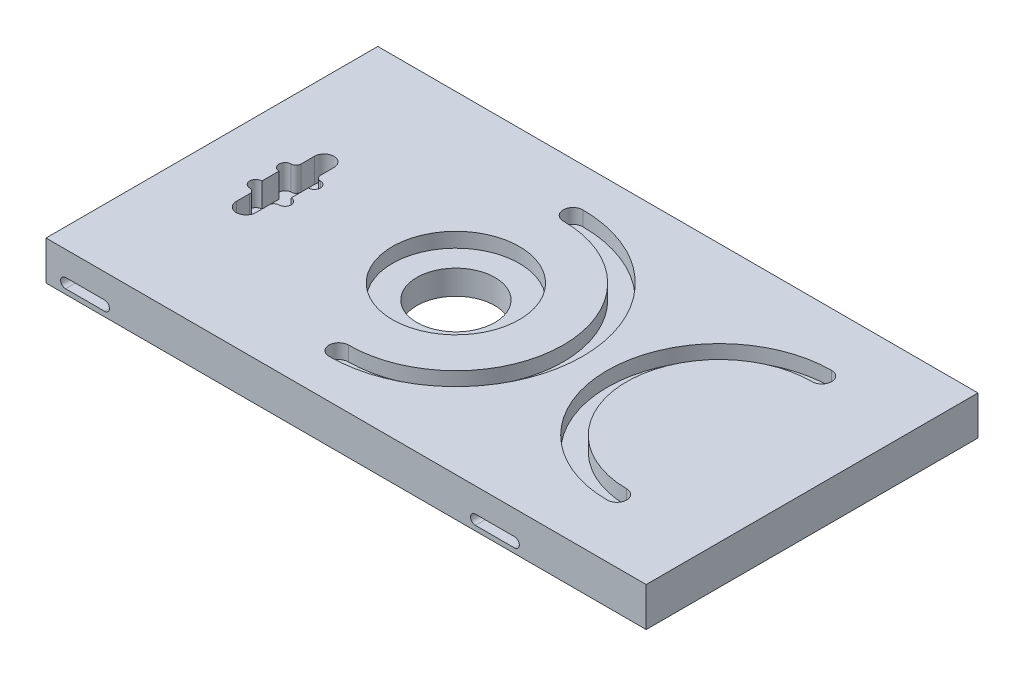
SolidWorks part; units mm, degrees
material "1060 Alloy"
ref_plane "Front Plane" through (0, 0, 0) normal (0, 0, 1) x (1, 0, 0)
ref_plane "Top Plane" through (0, 0, 0) normal (0, 1, 0) x (1, 0, 0)
ref_plane "Right Plane" through (0, 0, 0) normal (1, 0, 0) x (0, 0, -1)
sketch "Sketch1" plane through (0, 0, 0) normal (0, 1, 0) x (1, 0, 0)
  line L1 (-61.5, 34) -> (61.5, 34)
  line L2 (-61.5, 34) -> (-61.5, -34)
  line L3 (-61.5, -34) -> (61.5, -34)
  line L4 (61.5, 34) -> (61.5, -34)
  line L5 (-61.5, 34) -> (61.5, -34) construction
  line L6 (-61.5, -34) -> (61.5, 34) construction
  point P0 (0, 0)
  dimension "D1" = 68
  dimension "D2" = 123
extrude "Boss-Extrude1" add sketch "Sketch1" along normal blind 8
sketch "Sketch6" plane through (0, 0, -34) normal (0, 0, -1) x (-1, 0, 0)
  line L6 (49.5, 2) -> (57.5, 2) construction
  line L7 (49.5, 3) -> (57.5, 3)
  line L8 (49.5, 1) -> (57.5, 1)
  line L9 (61.5, 8) -> (61.5, 0) construction
  line L10 (55, 0) -> (-55, 0) construction
  arc A0 (49.5, 3) -> (49.5, 1) centre (49.5, 2) ccw
  arc A1 (57.5, 1) -> (57.5, 3) centre (57.5, 2) ccw
  point P2 (53.5, 2)
  dimension "D2" = 1
  dimension "D1" = 8
  dimension "D3" = 4
  dimension "D4" = 2
extrude "Cut-Extrude1" cut sketch "Sketch6" against normal blind 5
mirror "Mirror16" about plane through (0, 0, 0) normal (0, 0, 1) of "Cut-Extrude1"
pattern_linear "LPattern6" count 2 spacing 84 along (1, 0, 0) of "Mirror16", "Cut-Extrude1"
sketch "Sketch7" plane through (0, 8, 0) normal (0, 1, 0) x (1, 0, 0)
  line L0 (-44.2539, 0) -> (44.2539, 0) construction
  line L1 (-61.5, 34) -> (-61.5, -34) construction
  circle A0 centre (-11.5, 0) radius 8
  dimension "D1" = 50
extrude "Cut-Extrude2" cut sketch "Sketch7" against normal blind 10
sketch "Sketch8" plane through (0, 8, 0) normal (0, 1, 0) x (1, 0, 0)
  circle A0 centre (-11.5, 0) radius 13
extrude "Cut-Extrude3" cut sketch "Sketch8" against normal blind 3
sketch "Sketch9" plane through (0, 8, 0) normal (0, 1, 0) x (1, 0, 0)
  line L0 (-46.5, 8) -> (-46.5, -8) construction
  line L1 (-44.2539, 0) -> (44.2539, 0) construction
  line L2 (-44.5, 8) -> (-44.5, -8)
  line L3 (-48.5, 8) -> (-48.5, -8)
  arc A0 (-44.5, 8) -> (-48.5, 8) centre (-46.5, 8) ccw
  arc A1 (-48.5, -8) -> (-44.5, -8) centre (-46.5, -8) ccw
  circle A3 centre (-11.5, 0) radius 13 construction
  point P4 (-46.5, 0)
  dimension "D3" = 2
  dimension "D1" = 35
  dimension "D2" = 16
extrude "Cut-Extrude4" cut sketch "Sketch9" against normal blind 5
sketch "Sketch10" plane through (0, 8, 0) normal (0, 1, 0) x (1, 0, 0)
  line L0 (-44.2539, 0) -> (44.2539, 0) construction
  arc A0 (42.5, -21) -> (42.5, 21) centre (42.5, 0) cw construction
  arc A1 (42.5, 23) -> (42.5, -23) centre (42.5, 0) ccw
  arc A2 (42.5, 19) -> (42.5, -19) centre (42.5, 0) ccw
  arc A3 (42.5, 19) -> (42.5, 23) centre (42.5, 21) ccw
  arc A4 (42.5, -23) -> (42.5, -19) centre (42.5, -21) ccw
  circle A5 centre (-11.5, 0) radius 13 construction
  point P5 (21.5, 0)
  dimension "D1" = 54
  dimension "D2" = 19
  dimension "D3" = 23
extrude "Cut-Extrude5" cut sketch "Sketch10" against normal blind 3
sketch "Sketch11" plane through (0, 8, 0) normal (0, 1, 0) x (1, 0, 0)
  arc A0 (-11.5, -24) -> (-11.5, 24) centre (-11.5, 0) ccw construction
  arc A1 (-11.5, -26) -> (-11.5, 26) centre (-11.5, 0) ccw
  arc A2 (-11.5, -22) -> (-11.5, 22) centre (-11.5, 0) ccw
  arc A3 (-11.5, -22) -> (-11.5, -26) centre (-11.5, -24) ccw
  arc A4 (-11.5, 26) -> (-11.5, 22) centre (-11.5, 24) ccw
  point P4 (12.5, 0)
  dimension "D1" = 24
  dimension "D2" = 2
extrude "Cut-Extrude6" cut sketch "Sketch11" against normal blind 3
sketch "Sketch12" plane through (0, 8, 0) normal (0, 1, 0) x (1, 0, 0)
  line L0 (-44.2539, 0) -> (44.2539, 0) construction
  line L1 (-48.25, 3) -> (-44.75, 3)
  line L2 (-49.5, 1.75) -> (-49.5, -1.75)
  line L3 (-48.25, -3) -> (-44.75, -3)
  line L4 (-43.5, 1.75) -> (-43.5, -1.75)
  line L5 (-49.5, 3) -> (-43.5, -3) construction
  line L6 (-49.5, -3) -> (-43.5, 3) construction
  line L8 (-61.5, 34) -> (-61.5, -34) construction
  arc A0 (-48.25, 3) -> (-49.5, 1.75) centre (-49.5, 3) ccw
  arc A1 (-49.5, -1.75) -> (-48.25, -3) centre (-49.5, -3) ccw
  arc A2 (-44.75, -3) -> (-43.5, -1.75) centre (-43.5, -3) ccw
  arc A3 (-43.5, 1.75) -> (-44.75, 3) centre (-43.5, 3) ccw
  point P0 (-46.5, 0)
  dimension "D3" = 2.5
  dimension "D4" = 2.5
  dimension "D5" = 2.5
  dimension "D6" = 2.5
  dimension "D1" = 6
  dimension "D2" = 15
  dimension "6" = 6
extrude "Cut-Extrude7" cut sketch "Sketch12" against normal blind 5
fillet "Fillet2" radius 1 4 edges at (-48.5, 5.5, -3.75) (-44.5, 5.5, -3.75) (-44.5, 5.5, 3.75) (-48.5, 5.5, 3.75)
